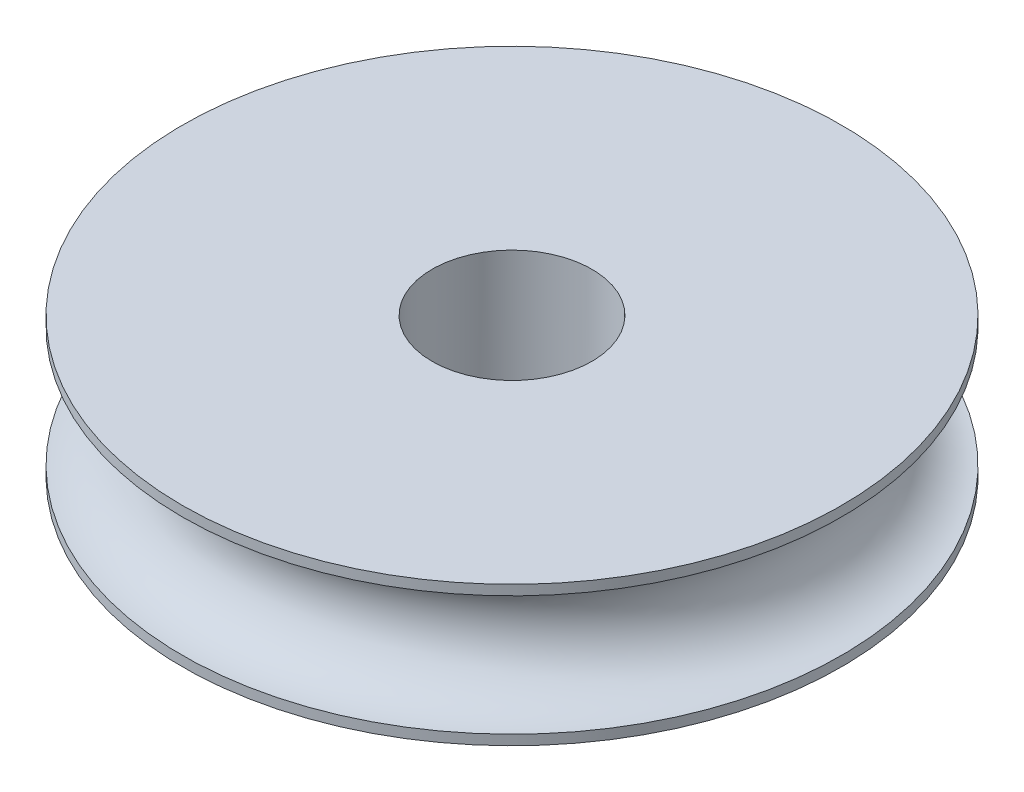
SolidWorks part; units mm, degrees
ref_plane "Front Plane" through (0, 0, 0) normal (0, 0, 1) x (1, 0, 0)
ref_plane "Top Plane" through (0, 0, 0) normal (0, 1, 0) x (1, 0, 0)
ref_plane "Right Plane" through (0, 0, 0) normal (1, 0, 0) x (0, 0, -1)
sketch "Sketch1" plane through (0, 0, 0) normal (0, 0, 1) x (1, 0, 0)
  line L0 (13.5, 6) -> (22.418, 6) construction
  line L1 (0, 0) -> (13.5, 0)
  line L2 (0, 0) -> (0, 6)
  line L3 (0, 6) -> (13.5, 6)
  line L4 (13.5, 0) -> (13.5, 6)
  line L5 (13.5, 0) -> (22.418, 0) construction
  line L6 (13.5, 6) -> (13.5, 0) construction
  line L7 (13.5, 12) -> (13.5, 0)
  line L8 (13.5, 6) -> (13.5, 0) construction
  line L9 (13.5, 12) -> (13.5, 0)
  line L10 (13.5, 3) -> (21.2573, 3)
  line L11 (13.5, 6) -> (16.5, 6)
  line L12 (13.5, 0) -> (16.5, 0)
  circle A0 centre (16.5, 3) radius 3
  point P10 (13.5, 6)
  point P11 (13.5, 6)
revolve "Revolve1" add sketch "Sketch1" angle 360 about L2
sketch "Sketch2" plane through (0, 6, 0) normal (0, 1, 0) x (1, 0, 0)
  circle A0 centre (0, 0) radius 16.5
extrude "Boss-Extrude1" add sketch "Sketch2" along normal blind 0.5
sketch "Sketch3" plane through (0, 0, 0) normal (0, -1, 0) x (1, 0, 0)
  circle A0 centre (0, 0) radius 16.5
extrude "Boss-Extrude2" add sketch "Sketch3" along normal blind 0.5
sketch "Sketch4" plane through (0, -0.5, 0) normal (0, -1, 0) x (1, 0, 0)
  circle A0 centre (0, 0) radius 1
extrude "Cut-Extrude1" cut sketch "Sketch4" against normal up to surface (7 mm away) up to face at (0, 6.5, 16.5)
sketch "Sketch5" plane through (0, 6.5, 0) normal (0, 1, 0) x (1, 0, 0)
  circle A0 centre (0, 0) radius 4
extrude "Cut-Extrude2" cut sketch "Sketch5" against normal blind 10
